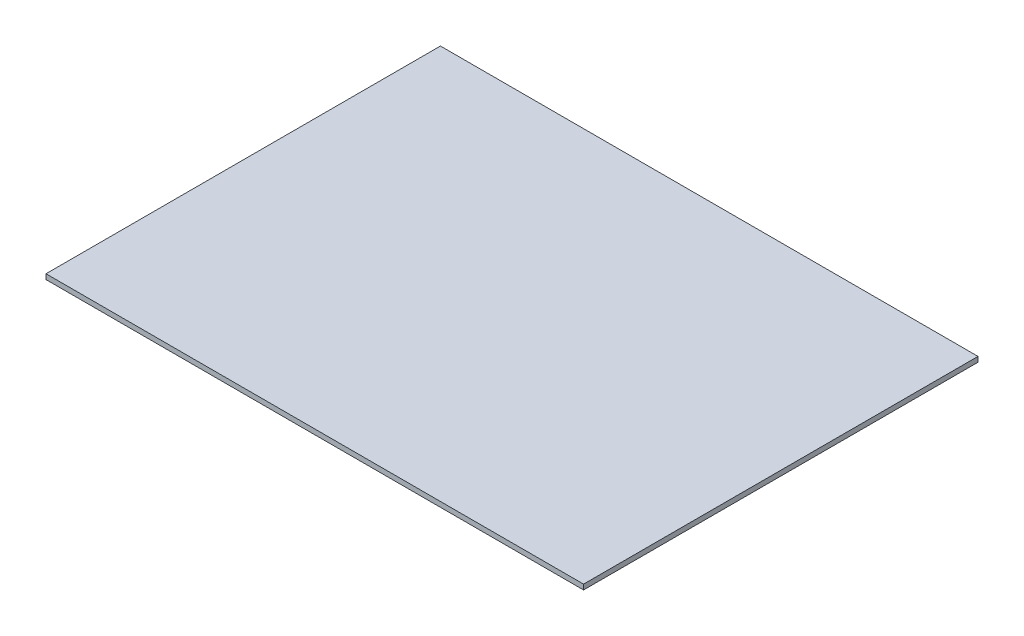
SolidWorks part; units mm, degrees
ref_plane "Front" through (0, 0, 0) normal (0, 0, 1) x (1, 0, 0)
ref_plane "Top" through (0, 0, 0) normal (0, 1, 0) x (1, 0, 0)
ref_plane "Right" through (0, 0, 0) normal (1, 0, 0) x (0, 0, -1)
sketch "Sketch1" plane through (0, 0, 0) normal (0, 1, 0) x (1, 0, 0)
  line L1 (0, 0) -> (167.64, 0)
  line L2 (0, 0) -> (0, 123)
  line L3 (0, 123) -> (167.64, 123)
  line L4 (167.64, 0) -> (167.64, 123)
  dimension "D1" = 167.64
  dimension "D2" = 123
extrude "Boss-Extrude1" add sketch "Sketch1" along normal blind 1.5875
